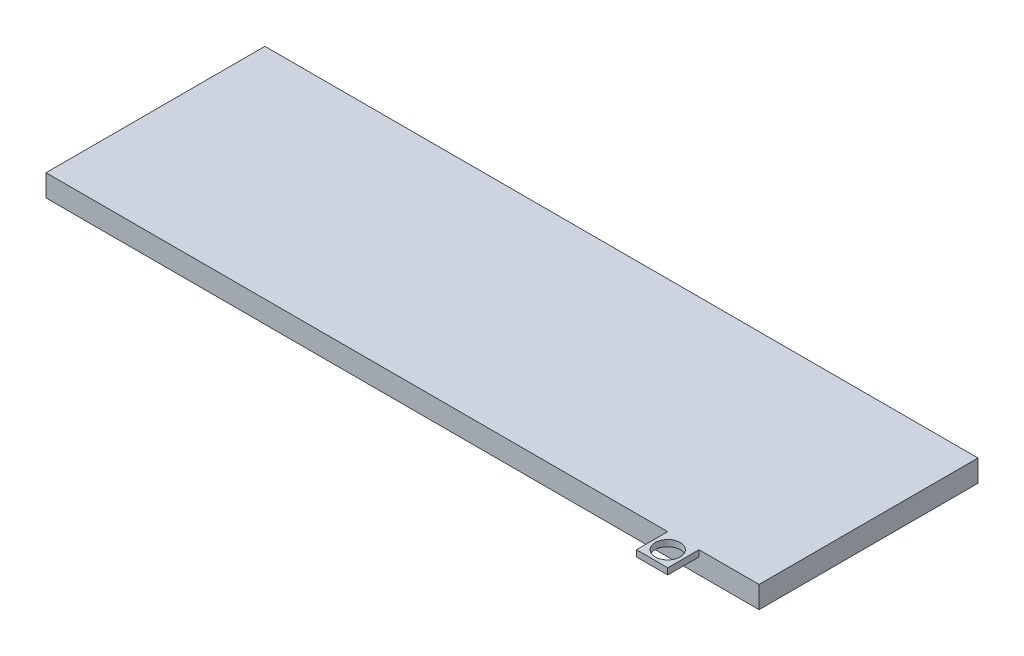
SolidWorks part; units mm, degrees
ref_plane "Plan de face" through (0, 0, 0) normal (0, 0, 1) x (1, 0, 0)
ref_plane "Plan de dessus" through (0, 0, 0) normal (0, 1, 0) x (1, 0, 0)
ref_plane "Plan de droite" through (0, 0, 0) normal (1, 0, 0) x (0, 0, -1)
sketch "Esquisse1" plane through (0, 0, 0) normal (0, 0, 1) x (1, 0, 0)
  line L0 (-115.0726, 3.1265) -> (-115.0726, -3.8735)
  line L1 (112.9274, 3.1265) -> (-115.0726, 3.1265)
  line L2 (112.9274, 3.1265) -> (112.9274, -3.8735)
  line L3 (110.9274, 1.1265) -> (110.9274, -3.8735)
  line L4 (110.9274, 1.1265) -> (-113.0726, 1.1265)
  line L5 (-113.0726, 1.1265) -> (-113.0726, -3.8735)
  line L6 (-115.0726, -3.8735) -> (-113.0726, -3.8735)
  line L7 (110.9274, -3.8735) -> (112.9274, -3.8735)
extrude "Boss.-Extru.1" add sketch "Esquisse1" along normal blind 70
sketch "Esquisse3" plane through (0, 0, 0) normal (0, 0, -1) x (-1, 0, 0)
  line L0 (113.0726, -3.8735) -> (113.0726, 1.1265) construction
  line L1 (113.0726, 1.1265) -> (-110.9274, 1.1265) construction
  line L2 (113.0726, -3.8735) -> (113.0726, 1.1265)
  line L3 (113.0726, 1.1265) -> (-110.9274, 1.1265)
  line L4 (-110.9274, 1.1265) -> (-110.9274, -3.8735) construction
  line L5 (-110.9274, 1.1265) -> (-110.9274, -3.8735)
  line L6 (-110.9274, -3.8735) -> (113.0726, -3.8735)
extrude "Boss.-Extru.2" add sketch "Esquisse3" against normal blind 2
sketch "Esquisse5" plane through (0, 1.1265, 0) normal (0, -1, 0) x (1, 0, 0)
  line L0 (-113.0726, 70) -> (110.9274, 70) construction
  line L1 (83.7182, 70) -> (93.7182, 70)
  line L2 (83.7182, 70) -> (83.7182, 80)
  line L3 (83.7182, 80) -> (93.7182, 80)
  line L4 (93.7182, 70) -> (93.7182, 80)
  circle A0 centre (88.7182, 75) radius 4
  dimension "D3" = 8
  dimension "D1" = 10
  dimension "D2" = 10
extrude "Boss.-Extru.3" add sketch "Esquisse5" against normal through all
sketch "Esquisse6" plane through (0, 0, 70) normal (0, 0, 1) x (1, 0, 0)
  line L0 (-113.0726, -3.8735) -> (110.9274, -3.8735)
  line L2 (-113.0726, -3.8735) -> (-113.0726, 1.1265) construction
  line L3 (-113.0726, 1.1265) -> (110.9274, 1.1265) construction
  line L4 (110.9274, 1.1265) -> (110.9274, -3.8735) construction
  line L5 (-113.0726, -3.8735) -> (-113.0726, 1.1265)
  line L6 (-113.0726, 1.1265) -> (110.9274, 1.1265)
  line L7 (110.9274, 1.1265) -> (110.9274, -3.8735)
  point P5 (0, 0)
extrude "Boss.-Extru.4" add sketch "Esquisse6" against normal blind 2
